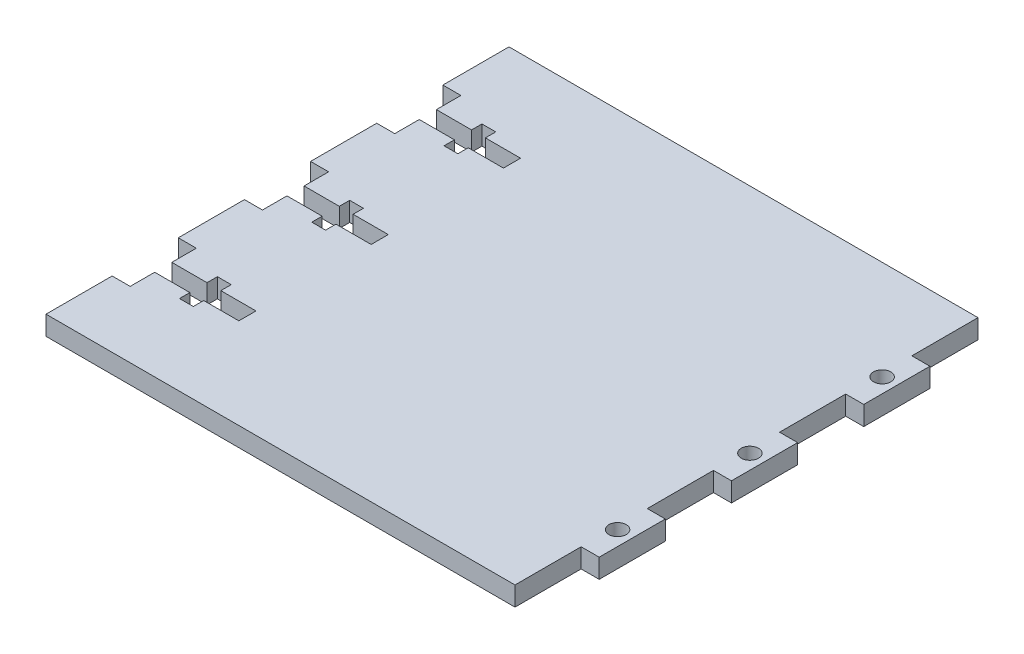
SolidWorks part; units mm, degrees
ref_plane "Front Plane" through (0, 0, 0) normal (0, 0, 1) x (1, 0, 0)
ref_plane "Top Plane" through (0, 0, 0) normal (0, 1, 0) x (1, 0, 0)
ref_plane "Right Plane" through (0, 0, 0) normal (1, 0, 0) x (0, 0, -1)
sketch "Sketch1" plane through (0, 0, 0) normal (0, 1, 0) x (1, 0, 0)
  line L0 (0, -38.5) -> (0, 38.5)
  line L1 (37.5, 0) -> (-37.5, 0)
  line L2 (-37.5, 38.5) -> (-37.5, -38.5)
  line L3 (-37.5, -38.5) -> (37.5, -38.5)
  line L4 (37.5, -38.5) -> (37.5, 38.5)
  line L5 (37.5, 38.5) -> (-37.5, 38.5)
  point P4 (0, 0)
  point P8 (0, 0)
extrude "Boss-Extrude1" add sketch "Sketch1" along normal blind 3.2 contours L2 L3 L4 L5
sketch "Sketch2" plane through (0, 3.2, 0) normal (0, 1, 0) x (1, 0, 0)
  line L0 (-37.5, 38.5) -> (-40.5, 38.5)
  line L1 (-40.5, 38.5) -> (-40.5, 27.5)
  line L2 (-40.5, 27.5) -> (-37.5, 27.5)
  line L3 (-37.5, 38.5) -> (-37.5, -38.5) construction
  line L4 (-37.5, 27.5) -> (-37.5, 38.5)
  line L5 (37.5, 38.5) -> (40.5, 38.5)
  line L6 (40.5, 38.5) -> (40.5, 27.5)
  line L7 (40.5, 27.5) -> (37.5, 27.5)
  line L8 (37.5, -38.5) -> (37.5, 38.5) construction
  line L9 (37.5, 27.5) -> (37.5, 38.5)
extrude "Boss-Extrude3" add sketch "Sketch2" against normal blind 3.2 contours L1 L2 L4 L0
pattern_linear "LPattern1" count 4 spacing 22 along (0, 0, 1) of "Boss-Extrude3"
sketch "Sketch4" plane through (0, 3.2, 0) normal (0, 1, 0) x (1, 0, 0)
  line L0 (40.5, 27.5) -> (40.5, 16.5)
  line L1 (40.5, 16.5) -> (37.5, 16.5)
  line L2 (40.5, 27.5) -> (37.5, 27.5)
  line L3 (37.5, -38.5) -> (37.5, 38.5) construction
  line L4 (37.5, 16.5) -> (37.5, 27.5)
sketch "Sketch5" plane through (0, 3.2, 0) normal (0, 1, 0) x (1, 0, 0)
  line L0 (-37.5, 27.5) -> (-37.5, 22)
  line L2 (-37.5, 27.5) -> (-37.5, 16.5) construction
  line L3 (-37.5, 20.575) -> (-37.5, 23.425)
  line L4 (-37.5, 22) -> (-23.5, 22)
  line L5 (-23.5, 20.575) -> (-23.5, 23.425)
  line L6 (-23.5, 23.425) -> (-37.5, 23.425)
  line L7 (-37.5, 20.575) -> (-23.5, 20.575)
  line L8 (-30.5, 18.85) -> (-30.5, 25.15)
  line L9 (-29.35, 25.15) -> (-31.65, 25.15)
  line L10 (-29.35, 18.85) -> (-31.65, 18.85)
  line L11 (-31.65, 18.85) -> (-31.65, 25.15)
  line L12 (-29.35, 18.85) -> (-29.35, 25.15)
  point P9 (-37.5, 22)
  point P13 (-23.5, 22)
  point P16 (-30.5, 22)
  point P19 (-30.5, 25.15)
  point P22 (-30.5, 18.85)
extrude "Cut-Extrude1" cut sketch "Sketch5" against normal through all contours L7 L5 L6 L3 | L11 L9 L12 L10
pattern_linear "LPattern3" count 3 spacing 22 along (0, 0, 1) of "Cut-Extrude1"
extrude "Boss-Extrude6" add sketch "Sketch4" against normal blind 3.2 contours L0 L1 L4 L2
sketch "Sketch7" plane through (0, 3.2, 0) normal (0, 1, 0) x (1, 0, 0)
  line L0 (37.5, 27.5) -> (37.5, 22)
  line L1 (40.5, 27.5) -> (40.5, 16.5) construction
  circle A0 centre (38.06, 22) radius 1.44
  dimension "D1" = 2.44
extrude "Cut-Extrude2" cut sketch "Sketch7" against normal through all contours A0
pattern_linear "LPattern7" count 3 spacing 22 along (0, 0, 1) of "Boss-Extrude6"
pattern_linear "LPattern8" count 3 spacing 22 along (0, 0, 1) of "Cut-Extrude2"
